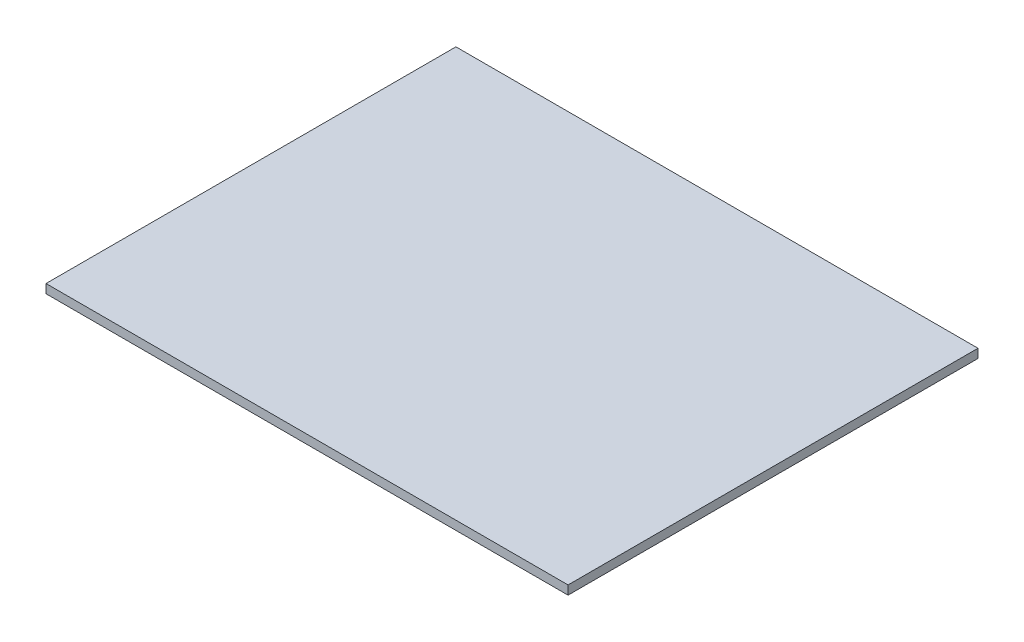
SolidWorks part; units mm, degrees
ref_plane "Front Plane" through (0, 0, 0) normal (0, 0, 1) x (1, 0, 0)
ref_plane "Top Plane" through (0, 0, 0) normal (0, 1, 0) x (1, 0, 0)
ref_plane "Right Plane" through (0, 0, 0) normal (1, 0, 0) x (0, 0, -1)
sketch "Sketch1" plane through (0, 263.6867, 0) normal (0, -1, 0) x (1, 0, 0)
  line L0 (19.2937, 1069.2039) -> (19.2937, 482.4639)
  line L1 (19.2937, 482.4639) -> (766.5363, 482.4639)
  line L2 (766.5363, 482.4639) -> (766.5363, 1069.2039)
  line L3 (766.5363, 1069.2039) -> (19.2937, 1069.2039)
  point P4 (0, 0)
  point P9 (0, 0)
  point P10 (0, 0)
  point P11 (0, 0)
  dimension "D1" = 586.74
  dimension "D2" = 747.2426
extrude "Boss-Extrude1" add sketch "Sketch1" against normal blind 12.7
equation "\"WOOD_THICKNESS\"=0.5"
equation "\"D1@Boss-Extrude1\"=\"WOOD_THICKNESS\""
equation "\"BOTTOM_SHORT_SIDE\"=23.1"
equation "\"D1@Sketch1\"=\"BOTTOM_SHORT_SIDE\""
equation "\"BOTTOM_LONG_SIDE\"=29.419"
equation "\"D2@Sketch1\"=\"BOTTOM_LONG_SIDE\""
